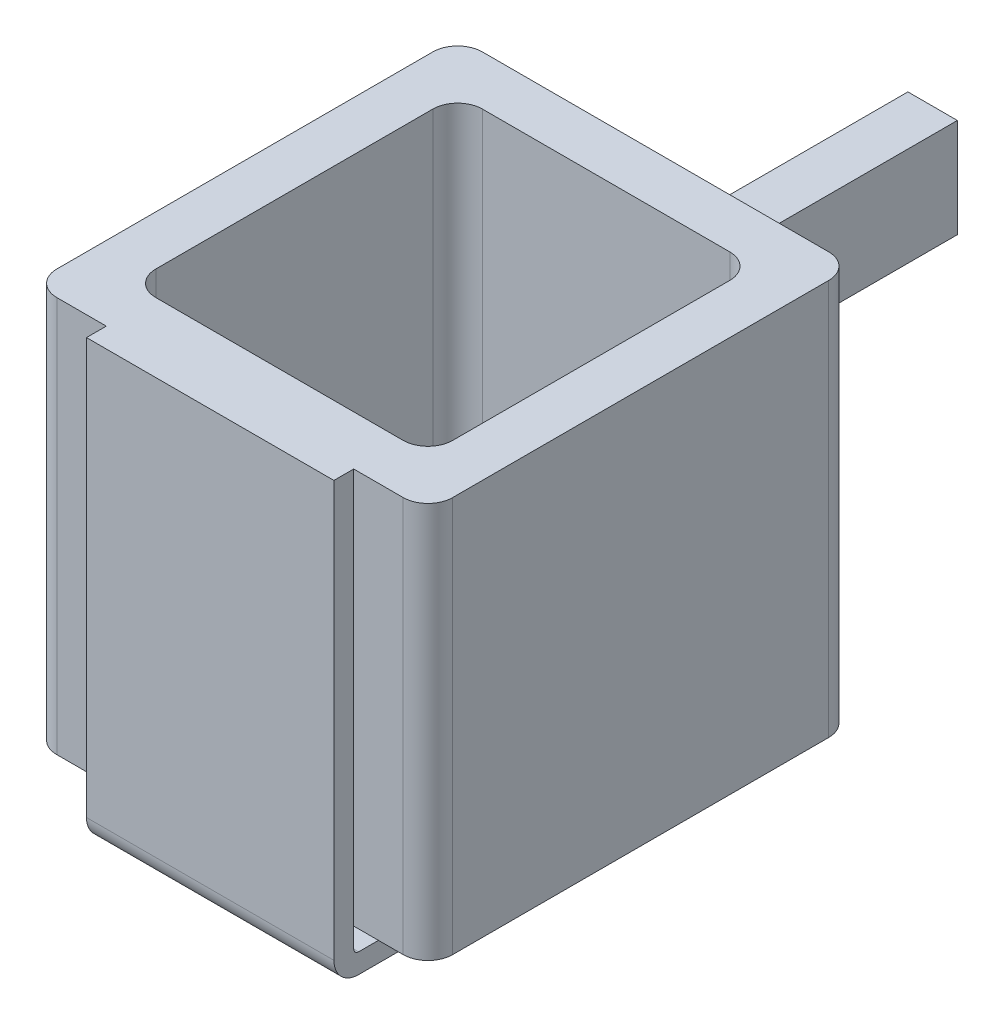
SolidWorks part; units mm, degrees
ref_plane "Спереди" through (0, 0, 0) normal (0, 0, 1) x (1, 0, 0)
ref_plane "Сверху" through (0, 0, 0) normal (0, 1, 0) x (1, 0, 0)
ref_plane "Справа" through (0, 0, 0) normal (1, 0, 0) x (0, 0, -1)
ref_plane "Плоскость1" through (-2, 0, 0) normal (-1, 0, 0) x (0, -1, 0)
sketch "Эскиз1" plane through (-2, 0, 0) normal (-1, 0, 0) x (0, -1, 0)
  line L0 (-2, 4.5) -> (-2, 0)
  line L1 (-2, 0) -> (2, 0)
  line L2 (2, 0) -> (2, 4.5)
  line L3 (2, 4.5) -> (-2, 4.5)
extrude "Бобышка-Вытянуть1" add sketch "Эскиз1" against normal blind 4
ref_plane "Плоскость3" through (0, 0, 0) normal (0, -1, 0) x (-1, 0, 0)
sketch "Эскиз2" plane through (0, -2, 0) normal (0, -1, 0) x (1, 0, 0)
  line L0 (-1.25, 4.3) -> (-1.25, 4.5)
  line L1 (-1.25, 4.5) -> (-2, 4.5)
  line L2 (-2, 4.5) -> (-2, 4.3)
  line L3 (-2, 4.3) -> (-1.25, 4.3)
extrude "Вырез-Вытянуть1" cut sketch "Эскиз2" against normal through all
sketch "Эскиз3" plane through (0, -2, 0) normal (0, -1, 0) x (1, 0, 0)
  line L0 (1.25, 4.5) -> (1.25, 4.3)
  line L1 (1.25, 4.3) -> (2, 4.3)
  line L2 (2, 4.3) -> (2, 4.5)
  line L3 (2, 4.5) -> (1.25, 4.5)
extrude "Вырез-Вытянуть2" cut sketch "Эскиз3" against normal blind 4
sketch "Эскиз4" plane through (0, -2, 0) normal (0, -1, 0) x (1, 0, 0)
  line L0 (-1.25, 4.3) -> (-1.25, 4.5)
  line L1 (-1.25, 4.5) -> (1.25, 4.5)
  line L2 (1.25, 4.5) -> (1.25, 4.3)
  line L3 (1.25, 4.3) -> (-1.25, 4.3)
extrude "Бобышка-Вытянуть2" add sketch "Эскиз4" along normal blind 0.45
sketch "Эскиз5" plane through (0, 0, 4.3) normal (0, 0, -1) x (-1, 0, 0)
  line L0 (1.25, -2.25) -> (1.25, -2.45)
  line L1 (1.25, -2.45) -> (-1.25, -2.45)
  line L2 (-1.25, -2.45) -> (-1.25, -2.25)
  line L3 (-1.25, -2.25) -> (1.25, -2.25)
extrude "Бобышка-Вытянуть3" add sketch "Эскиз5" along normal blind 1.7073
sketch "Эскиз6" plane through (0, -2, 0) normal (0, -1, 0) x (1, 0, 0)
  line L0 (-1.5, 0.5) -> (1.5, 0.5)
  line L1 (1.5, 0.5) -> (1.5, 3.8)
  line L2 (1.5, 3.8) -> (-1.5, 3.8)
  line L3 (-1.5, 3.8) -> (-1.5, 0.5)
extrude "Вырез-Вытянуть3" cut sketch "Эскиз6" against normal through all
sketch "Эскиз7" plane through (0, -2.25, 0) normal (0, 1, 0) x (-1, 0, 0)
  line L0 (1.25, 2.5927) -> (-1.25, 2.5927)
  line L1 (-1.25, 2.5927) -> (-1.25, 2.7927)
  line L2 (-1.25, 2.7927) -> (1.25, 2.7927)
  line L3 (1.25, 2.7927) -> (1.25, 2.5927)
extrude "Бобышка-Вытянуть4" add sketch "Эскиз7" along normal blind 2.9682
ref_plane "Плоскость2" through (0, -0.5, 0) normal (0, -1, 0) x (1, 0, 0)
sketch "Эскиз8" plane through (0, 0, 0) normal (0, -1, 0) x (1, 0, 0)
  line L0 (-0.25, 0) -> (-0.25, -2.8)
  line L1 (-0.25, -2.8) -> (0, -3.05)
  line L2 (0, -3.05) -> (0.25, -2.8)
  line L3 (0.25, -2.8) -> (0.25, 0)
  line L4 (0.25, 0) -> (-0.25, 0)
extrude "Бобышка-Вытянуть5" add sketch "Эскиз8" against normal blind 1
chamfer "Фаска1" distance 0.0707 angle 45 1 edges at (0, 0.5, -3.05)
fillet "Скругление1" radius 0.05 2 edges at (0, -2.25, 2.7927) (0, -2.25, 4.3)
chamfer "Фаска2" distance 0.2 angle 45 2 edges at (0, 1, -3) (0, 0, -3)
fillet "Скругление2" radius 0.25 10 edges at (-2, 0, 0) (-1.5, 0, 0.5) (2, 0, 4.3) (0, -2.45, 2.5927) (-2, 0, 4.3) (0, -2.45, 4.5) (2, 0, 0) (1.5, 0, 3.8) (-1.5, 0, 3.8) (1.5, 0, 0.5)
